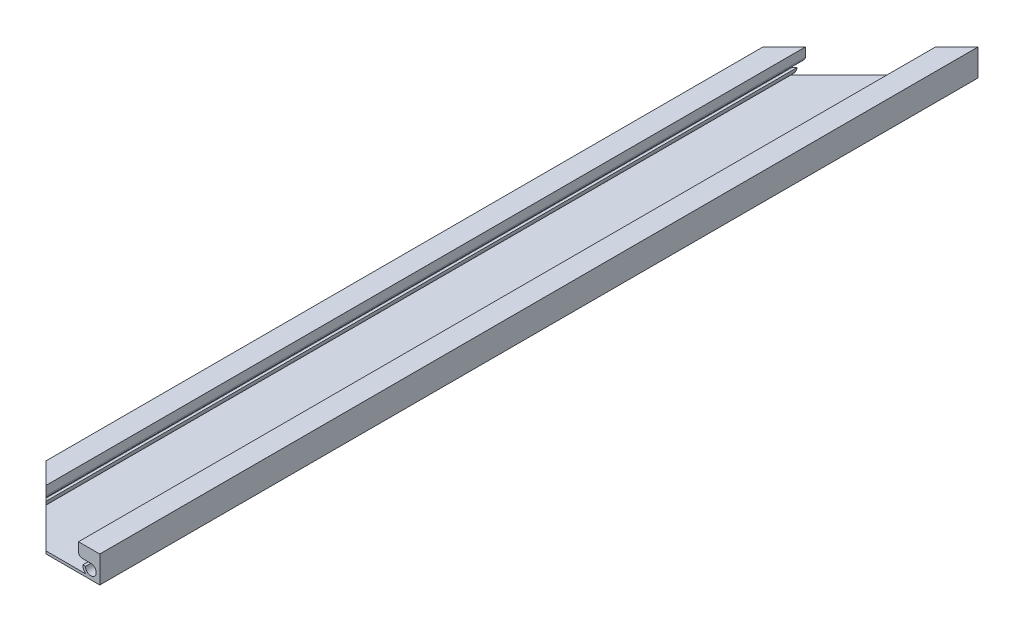
SolidWorks part; units mm, degrees
ref_plane "정면" through (0, 0, 0) normal (0, 0, 1) x (1, 0, 0)
ref_plane "윗면" through (0, 0, 0) normal (0, 1, 0) x (1, 0, 0)
ref_plane "우측면" through (0, 0, 0) normal (1, 0, 0) x (0, 0, -1)
sketch "스케치1" plane through (0, 0, 0) normal (0, 0, 1) x (1, 0, 0)
  line L1 (-30, 7.5) -> (30, 7.5)
  line L2 (-30, 7.5) -> (-30, -7.5)
  line L3 (-30, -7.5) -> (30, -7.5)
  line L4 (30, 7.5) -> (30, -7.5)
  line L5 (-30, 7.5) -> (30, -7.5) construction
  line L6 (-30, -7.5) -> (30, 7.5) construction
  point P0 (0, 0)
  dimension "D1" = 60
  dimension "D2" = 15
extrude "보스-돌출1" add sketch "스케치1" along normal blind 520
sketch "스케치2" plane through (0, 0, 0) normal (0, 0, -1) x (-1, 0, 0)
  line L0 (30, -7.5) -> (-30, -7.5) construction
  line L2 (-30, -7.5) -> (-30, 7.5) construction
  line L3 (30, 7.5) -> (30, -7.5) construction
  circle A0 centre (-25, -2.5) radius 3
  circle A1 centre (25, -2.5) radius 3
  dimension "D1" = 6
  dimension "D3" = 5
  dimension "D4" = 6
  dimension "D6" = 5
  dimension "D2" = 5
  dimension "D5" = 5
extrude "컷-돌출1" cut sketch "스케치2" against normal through all
sketch "스케치3" plane through (0, 0, 0) normal (0, 0, -1) x (-1, 0, 0)
  line L0 (-22.1716, -6) -> (22.1716, -6)
  line L1 (-20.5, -2.5) -> (-25, -2.5)
  line L2 (-25, -2.5) -> (-25, 0.5)
  line L3 (-25, 0.5) -> (25, 0.5)
  line L4 (25, 0.5) -> (25, -2.5)
  line L5 (25, -2.5) -> (20.5, -2.5)
  line L6 (30, -7.5) -> (-30, -7.5) construction
  arc A0 (22.1716, -6) -> (20.5, -2.5) centre (25, -2.5) cw
  arc A1 (-22.1716, -6) -> (-20.5, -2.5) centre (-25, -2.5) ccw
  circle A2 centre (-25, -2.5) radius 3 construction
  circle A3 centre (25, -2.5) radius 3 construction
  dimension "D2" = 1.5
  dimension "D1" = 1.5
  dimension "1.5" = 1.5
extrude "컷-돌출2" cut sketch "스케치3" against normal through all
sketch "스케치4" plane through (0, 0, 0) normal (0, 0, -1) x (-1, 0, 0)
  line L0 (-18.1431, 0.5) -> (18.1569, 0.5)
  line L1 (25, 0.5) -> (-25, 0.5) construction
  line L2 (-18.1431, 0.5) -> (-18.1431, 7.5)
  line L3 (-30, 7.5) -> (30, 7.5) construction
  line L4 (-18.1431, 7.5) -> (18.1569, 7.5)
  line L5 (18.1569, 7.5) -> (18.1569, 0.5)
  point P5 (0, 0)
  dimension "D1" = 36.3
extrude "컷-돌출3" cut sketch "스케치4" against normal through all
fillet "필렛1" radius 2 2 edges at (-18.1569, 0.5, 260) (18.1431, 0.5, 260)
sketch "스케치5" plane through (0, -7.5, 0) normal (0, -1, 0) x (1, 0, 0)
  line L0 (-30, 520) -> (-30, 460)
  line L1 (-30, 520) -> (-30, 0) construction
  line L2 (-30, 460) -> (30, 520)
  line L5 (-30, 0) -> (30, 0)
  line L6 (-30, 260) -> (30, 260) construction
  line L7 (30, 520) -> (30, 0) construction
  line L15 (-30, 520) -> (30, 520)
  line L17 (-30, 60) -> (30, 0)
  line L18 (-30, 0) -> (-30, 60)
  dimension "D1" = 45
extrude "컷-돌출4" cut sketch "스케치5" against normal through all
sketch "스케치7" plane through (0, -7.5, 0) normal (0, -1, 0) x (1, 0, 0)
  line L0 (-30, 460) -> (30, 520) construction
  line L5 (30, 520) -> (0, 520)
  line L6 (30, 520) -> (30, 490)
  line L7 (30, 490) -> (0, 490)
  line L8 (0, 520) -> (0, 490)
extrude "컷-돌출6" cut sketch "스케치7" against normal through all and the other way through all
